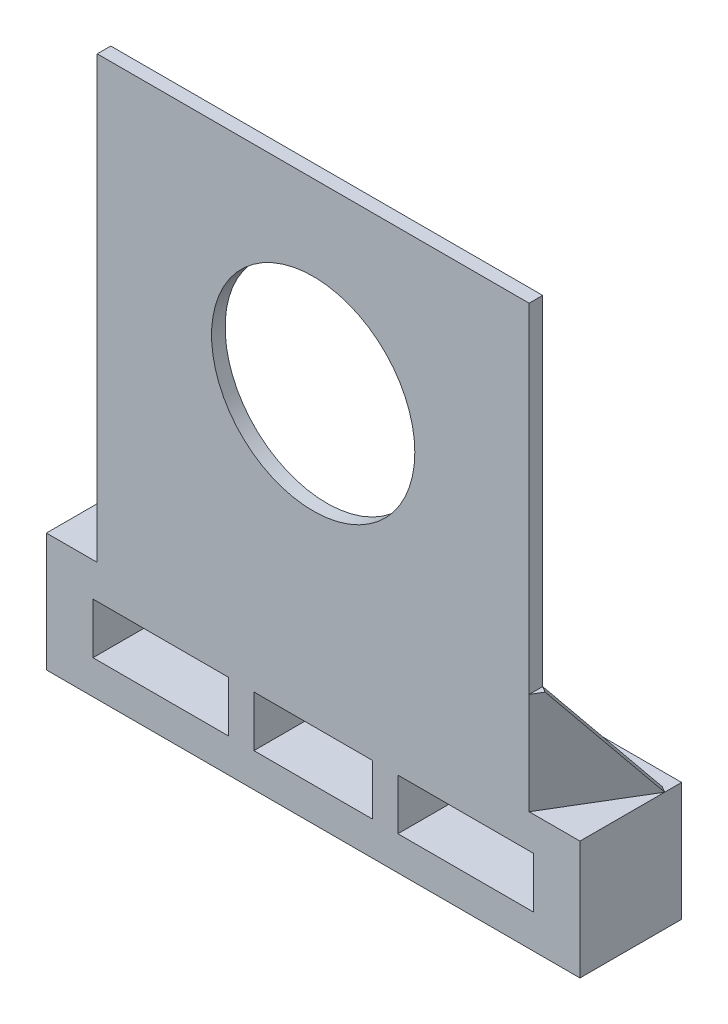
SolidWorks part; units mm, degrees
ref_plane "Front Plane" through (0, 0, 0) normal (0, 0, 1) x (1, 0, 0)
ref_plane "Top Plane" through (0, 0, 0) normal (0, 1, 0) x (1, 0, 0)
ref_plane "Right Plane" through (0, 0, 0) normal (1, 0, 0) x (0, 0, -1)
sketch "Sketch1" plane through (0, 0, 0) normal (0, 0, 1) x (1, 0, 0)
  line L1 (-127.5, 130) -> (127.5, 130)
  line L2 (-127.5, 130) -> (-127.5, -130)
  line L3 (-127.5, -130) -> (127.5, -130)
  line L4 (127.5, 130) -> (127.5, -130)
  line L5 (-127.5, 130) -> (127.5, -130) construction
  line L6 (-127.5, -130) -> (127.5, 130) construction
  circle A0 centre (0, 20) radius 60
  point P0 (0, 0)
  dimension "D3" = 120
  dimension "D1" = 255
  dimension "D2" = 260
  dimension "D4" = 110
  dimension "D5" = 20
extrude "Boss-Extrude1" add sketch "Sketch1" along normal blind 8
sketch "Sketch2" plane through (0, 0, 8) normal (0, 0, 1) x (1, 0, 0)
  line L0 (0, -130) -> (157.5, -130)
  line L1 (-127.5, -130) -> (127.5, -130) construction
  line L2 (157.5, -130) -> (157.5, -200)
  line L3 (157.5, -200) -> (-157.5, -200)
  line L4 (-157.5, -200) -> (-157.5, -130)
  line L5 (-157.5, -130) -> (0, -130)
  line L7 (-35, -150) -> (35, -150)
  line L8 (-35, -150) -> (-35, -180)
  line L9 (-35, -180) -> (35, -180)
  line L10 (35, -150) -> (35, -180)
  line L11 (-35, -150) -> (35, -180) construction
  line L12 (-35, -180) -> (35, -150) construction
  line L13 (50, -150) -> (130, -150)
  line L14 (50, -150) -> (50, -180)
  line L15 (50, -180) -> (130, -180)
  line L16 (130, -150) -> (130, -180)
  line L17 (50, -150) -> (130, -180) construction
  line L18 (50, -180) -> (130, -150) construction
  line L19 (-130, -150) -> (-50, -150)
  line L20 (-130, -150) -> (-130, -180)
  line L21 (-130, -180) -> (-50, -180)
  line L22 (-50, -150) -> (-50, -180)
  line L23 (-130, -150) -> (-50, -180) construction
  line L24 (-130, -180) -> (-50, -150) construction
  point P4 (0, -165)
  point P12 (90, -165)
  point P17 (-90, -165)
  point P22 (0, -150)
  point P24 (35, -165)
  dimension "D1" = 157.5
  dimension "D2" = 157.5
  dimension "D3" = 70
  dimension "D4" = 35
  dimension "D5" = 15
  dimension "D6" = 90
  dimension "D7" = 15
  dimension "D8" = 35
  dimension "D9" = 30
  dimension "D10" = 30
  dimension "D11" = 80
  dimension "D12" = 80
  dimension "D13" = 15
  dimension "D14" = 15
  dimension "D15" = 35
  dimension "D16" = 35
  dimension "D17" = 0
extrude "Boss-Extrude2" add sketch "Sketch2" against normal blind 60
sketch "Sketch3" plane through (0, -130, 0) normal (0, 1, 0) x (1, 0, 0)
  line L0 (127.5, -8) -> (157.5, 42)
  line L1 (157.5, 52) -> (157.5, -8) construction
  line L2 (157.5, -8) -> (127.5, -8) construction
  line L3 (127.5, -8) -> (127.5, 0)
  line L4 (127.5, 0) -> (153.9706, 44.1176)
  line L5 (157.5, 42) -> (153.9706, 44.1176)
  dimension "D1" = 50
extrude "Boss-Extrude3" add sketch "Sketch3" along normal blind 60
sketch "Sketch4" plane through (97.2794, 0, 58.3676) normal (0.8575, 0, 0.5145) x (0.5145, 0, -0.8575)
  line L0 (65.5982, -70) -> (117.0478, -130)
  line L1 (117.0478, -130) -> (117.0478, -70)
  line L2 (117.0478, -70) -> (65.5982, -70)
extrude "Cut-Extrude1" cut sketch "Sketch4" against normal blind 60
mirror "Mirror4" about plane through (0, 0, 0) normal (1, 0, 0) of "Boss-Extrude3"
sketch "Sketch5" plane through (-97.2794, 0, 58.3676) normal (-0.8575, 0, 0.5145) x (0.5145, 0, 0.8575)
  line L0 (-65.5982, -70) -> (-117.0478, -130)
  line L1 (-117.0478, -130) -> (-117.0478, -70)
  line L2 (-117.0478, -70) -> (-65.5982, -70)
extrude "Cut-Extrude2" cut sketch "Sketch5" against normal blind 60
